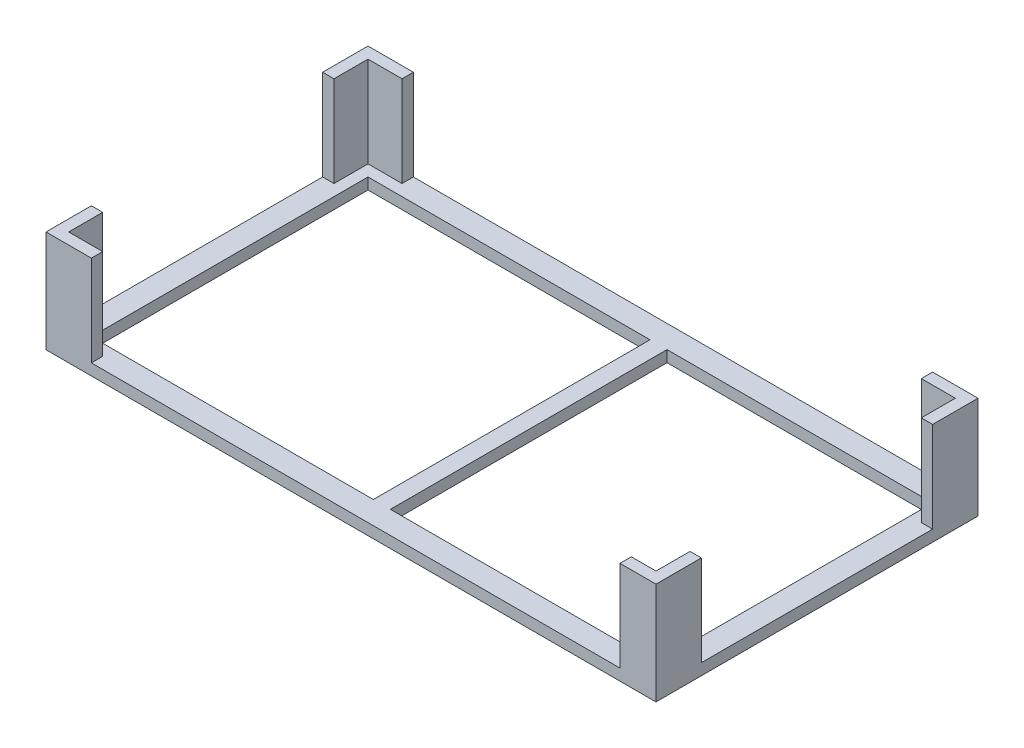
SolidWorks part; units mm, degrees
ref_plane "Front" through (0, 0, 0) normal (0, 0, 1) x (1, 0, 0)
ref_plane "Top" through (0, 0, 0) normal (0, 1, 0) x (1, 0, 0)
ref_plane "Right" through (0, 0, 0) normal (1, 0, 0) x (0, 0, -1)
sketch "草图1" plane through (0, 0, 0) normal (0, 1, 0) x (1, 0, 0)
  line L1 (0, 0) -> (53.8, 0)
  line L2 (0, 0) -> (0, -28.4)
  line L3 (0, -28.4) -> (53.8, -28.4)
  line L4 (53.8, 0) -> (53.8, -28.4)
  dimension "D1" = 53.8
  dimension "D2" = 28.4
extrude "凸台-拉伸1" add sketch "草图1" along normal blind 1
sketch "草图2" plane through (0, 1, 0) normal (0, 1, 0) x (1, 0, 0)
  line L1 (53.8, -28.4) -> (53.622, -28.4)
  line L2 (53.8, -28.4) -> (53.8, -24.4)
  line L3 (53.8, -24.4) -> (52.8, -24.4)
  line L4 (52.8, -27.4) -> (52.8, -24.4)
  line L5 (53.8, 0) -> (52.8, 0)
  line L6 (53.8, 0) -> (53.8, -4)
  line L7 (53.8, -4) -> (52.8, -4)
  line L8 (52.8, -1) -> (52.8, -4)
  line L9 (53.622, -28.4) -> (50.622, -28.4)
  line L10 (0, -27.4) -> (0, -24.4)
  line L11 (0, -24.4) -> (1, -24.4)
  line L12 (1, -27.4) -> (1, -24.4)
  line L13 (0, -28.4) -> (4, -28.4)
  line L14 (0, -28.4) -> (0, -27.4)
  line L15 (1, -27.4) -> (4, -27.4)
  line L16 (4, -28.4) -> (4, -27.4)
  line L17 (52.8, 0) -> (49.8, 0)
  line L18 (52.8, -27.4) -> (50.622, -27.4)
  line L19 (50.622, -28.4) -> (50.622, -27.4)
  line L20 (0, 0) -> (4, 0)
  line L21 (52.8, -1) -> (49.8, -1)
  line L22 (49.8, 0) -> (49.8, -1)
  line L23 (0, 0) -> (0, -1)
  line L24 (1, -1) -> (4, -1)
  line L25 (4, 0) -> (4, -1)
  line L27 (0, -1) -> (0, -4)
  line L28 (0, -4) -> (1, -4)
  line L29 (1, -1) -> (1, -4)
  dimension "D2" = 3
  dimension "D3" = 1
  dimension "D4" = 4
  dimension "D5" = 1
  dimension "D6" = 3
  dimension "D7" = 1
  dimension "D8" = 4
  dimension "D9" = 1
  dimension "D10" = 3
  dimension "D11" = 1
  dimension "D12" = 1
  dimension "D13" = 3
  dimension "D14" = 3
  dimension "D15" = 3
  dimension "D16" = 1
  dimension "D17" = 1
extrude "凸台-拉伸2" add sketch "草图2" along normal blind 8
sketch "草图4" plane through (0, 0, 0) normal (0, -1, 0) x (1, 0, 0)
  line L11 (28.373, 2) -> (51.8, 2)
  line L12 (26.873, 26.4) -> (2, 26.4)
  line L13 (28.373, 2) -> (28.373, 26.4)
  line L15 (2, 26.4) -> (2, 2)
  line L16 (51.8, 26.4) -> (2, 26.4)
  line L17 (51.8, 2) -> (51.8, 26.4)
  line L18 (2, 2) -> (51.8, 2)
  line L19 (2, 26.4) -> (2, 2)
  line L20 (51.8, 26.4) -> (28.373, 26.4)
  line L21 (51.8, 2) -> (51.8, 26.4)
  line L22 (2, 2) -> (26.873, 2)
  line L23 (26.873, 2) -> (26.873, 26.4)
  dimension "D2" = 1.5
  dimension "D1" = 2
extrude "切除-拉伸1" cut sketch "草图4" against normal through all
